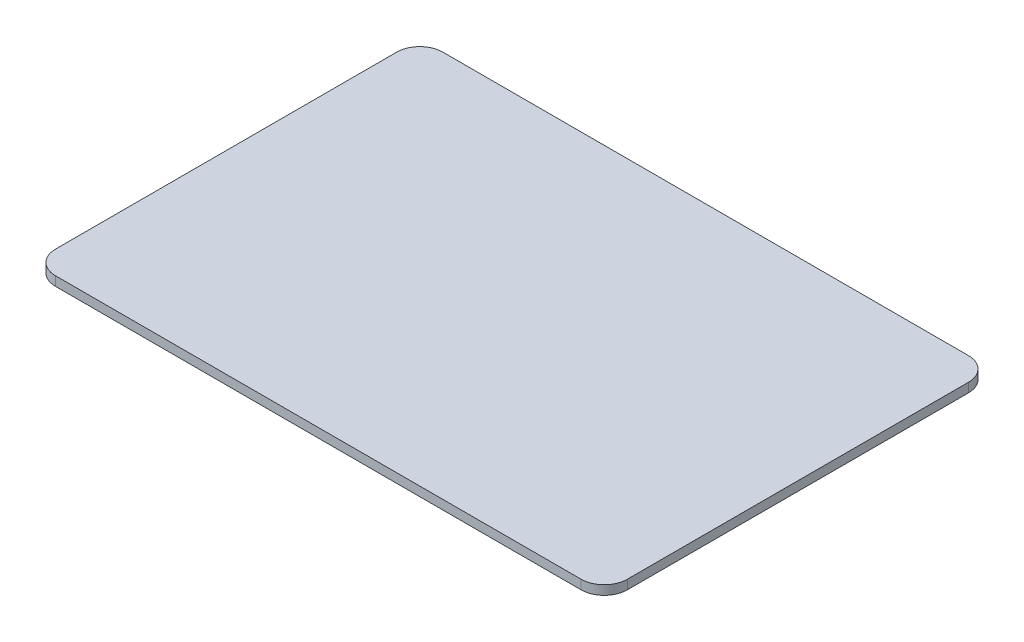
SolidWorks part; units mm, degrees
ref_plane "Front Plane" through (0, 0, 0) normal (0, 0, 1) x (1, 0, 0)
ref_plane "Top Plane" through (0, 0, 0) normal (0, 1, 0) x (1, 0, 0)
ref_plane "Right Plane" through (0, 0, 0) normal (1, 0, 0) x (0, 0, -1)
sketch "Sketch1" plane through (0, 0, 0) normal (0, 1, 0) x (1, 0, 0)
  line L1 (-62, 42) -> (62, 42)
  line L2 (-62, 42) -> (-62, -42)
  line L3 (-62, -42) -> (62, -42)
  line L4 (62, 42) -> (62, -42)
  line L5 (-62, 42) -> (62, -42) construction
  line L6 (-62, -42) -> (62, 42) construction
  point P0 (0, 0)
  dimension "D1" = 124
  dimension "D2" = 84
extrude "Boss-Extrude1" add sketch "Sketch1" along normal blind 2
fillet "Fillet1" radius 5 1 edges at (62, 1, 42)
fillet "Fillet2" radius 5 1 edges at (-62, 1, 42)
fillet "Fillet3" radius 5 1 edges at (-62, 1, -42)
fillet "Fillet4" radius 5 1 edges at (62, 1, -42)
